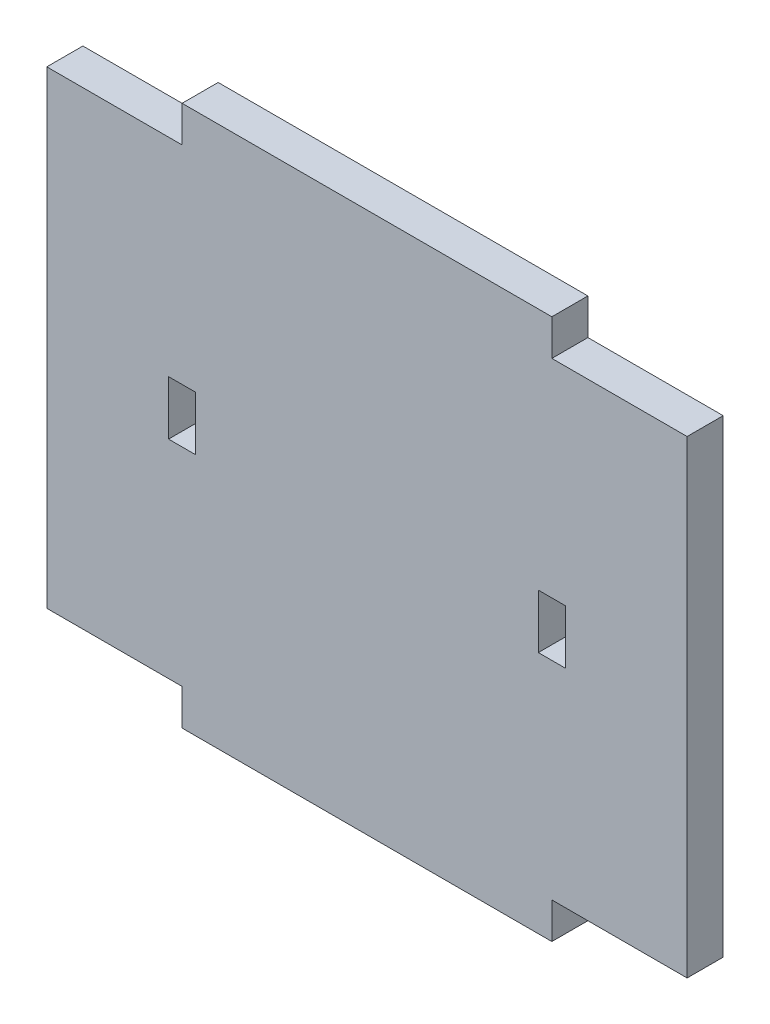
SolidWorks part; units mm, degrees
ref_plane "Front Plane" through (0, 0, 0) normal (0, 0, 1) x (1, 0, 0)
ref_plane "Top Plane" through (0, 0, 0) normal (0, 1, 0) x (1, 0, 0)
ref_plane "Right Plane" through (0, 0, 0) normal (1, 0, 0) x (0, 0, -1)
sketch "Sketch1" plane through (0, 0, 0) normal (0, 0, 1) x (1, 0, 0)
  line L0 (-13.2632, 0) -> (27.7368, 0)
  line L1 (27.7368, 0) -> (27.7368, 4)
  line L2 (27.7368, 4) -> (42.7368, 4)
  line L3 (42.7368, 4) -> (42.7368, 56)
  line L4 (42.7368, 56) -> (27.7368, 56)
  line L5 (27.7368, 56) -> (27.7368, 60)
  line L6 (27.7368, 60) -> (-13.2632, 60)
  line L7 (-13.2632, 60) -> (-13.2632, 56)
  line L8 (-13.2632, 56) -> (-28.2632, 56)
  line L9 (-28.2632, 56) -> (-28.2632, 4)
  line L10 (-28.2632, 4) -> (-13.2632, 4)
  line L11 (-13.2632, 4) -> (-13.2632, 0)
  dimension "D2" = 15
  dimension "D3" = 41
  dimension "D4" = 52
  dimension "D6" = 4
extrude "Boss-Extrude1" add sketch "Sketch1" along normal blind 4
sketch "Sketch2" plane through (0, 0, 4) normal (0, 0, 1) x (1, 0, 0)
  line L0 (-28.2632, 30) -> (42.7368, 30) construction
  line L1 (-14.7632, 33) -> (-11.7632, 33)
  line L2 (-14.7632, 33) -> (-14.7632, 27)
  line L3 (-14.7632, 27) -> (-11.7632, 27)
  line L4 (-11.7632, 33) -> (-11.7632, 27)
  line L5 (-28.2632, 56) -> (-28.2632, 4) construction
  line L6 (42.7368, 4) -> (42.7368, 56) construction
  line L7 (7.2368, 0) -> (7.2368, 60) construction
  line L8 (-13.2632, 0) -> (27.7368, 0) construction
  line L9 (27.7368, 60) -> (-13.2632, 60) construction
  line L10 (29.2368, 27) -> (26.2368, 27)
  line L11 (29.2368, 33) -> (26.2368, 33)
  line L12 (26.2368, 33) -> (26.2368, 27)
  line L13 (29.2368, 33) -> (29.2368, 27)
  dimension "D1" = 6
  dimension "D2" = 3
  dimension "D3" = 19
extrude "Cut-Extrude1" cut sketch "Sketch2" against normal blind 10
